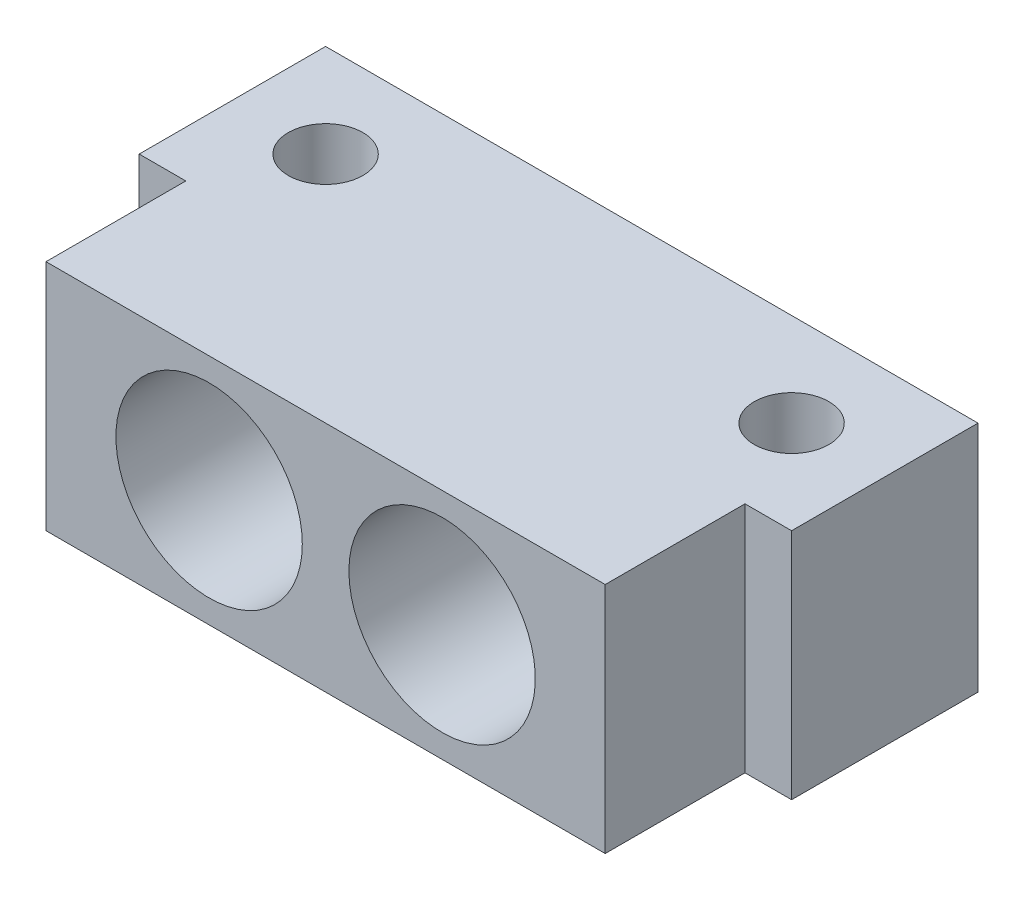
SolidWorks part; units mm, degrees
ref_plane "Front Plane" through (0, 0, 0) normal (0, 0, 1) x (1, 0, 0)
ref_plane "Top Plane" through (0, 0, 0) normal (0, 1, 0) x (1, 0, 0)
ref_plane "Right Plane" through (0, 0, 0) normal (1, 0, 0) x (0, 0, -1)
sketch "Sketch1" plane through (0, 0, 0) normal (0, 1, 0) x (1, 0, 0)
  line L0 (0, 10) -> (0, -10) construction
  line L1 (-35, -10) -> (-30, -10)
  line L2 (-35, -10) -> (-35, 10)
  line L3 (-35, 10) -> (35, 10)
  line L4 (35, -10) -> (35, 10)
  line L5 (-35, -10) -> (35, 10) construction
  line L6 (-35, 10) -> (35, -10) construction
  line L7 (-35, 0) -> (35, 0) construction
  line L8 (-30, -10) -> (-30, -25)
  line L9 (-30, -25) -> (30, -25)
  line L10 (30, -10) -> (30, -25)
  line L11 (30, -10) -> (35, -10)
  circle A0 centre (-25, 0) radius 4
  circle A1 centre (25, 0) radius 4
  point P0 (0, 0)
  point P19 (0, 0)
  dimension "D3" = 8
  dimension "D4" = 50
  dimension "D1" = 20
  dimension "D2" = 70
  dimension "D5" = 60
  dimension "D6" = 15
extrude "Boss-Extrude1" add sketch "Sketch1" along normal blind 25
sketch "Sketch2" plane through (0, 0, 25) normal (0, 0, 1) x (1, 0, 0)
  line L0 (-30, 12.5) -> (30, 12.5) construction
  line L1 (-30, 25) -> (-30, 0) construction
  line L2 (30, 25) -> (30, 0) construction
  line L3 (0, 25) -> (0, 0) construction
  line L4 (-30, 25) -> (30, 25) construction
  line L5 (-30, 0) -> (30, 0) construction
  circle A0 centre (-12.5, 12.5) radius 10
  circle A1 centre (12.5, 12.5) radius 10
  dimension "D1" = 20
  dimension "D2" = 25
extrude "Cut-Extrude1" cut sketch "Sketch2" against normal blind 15
